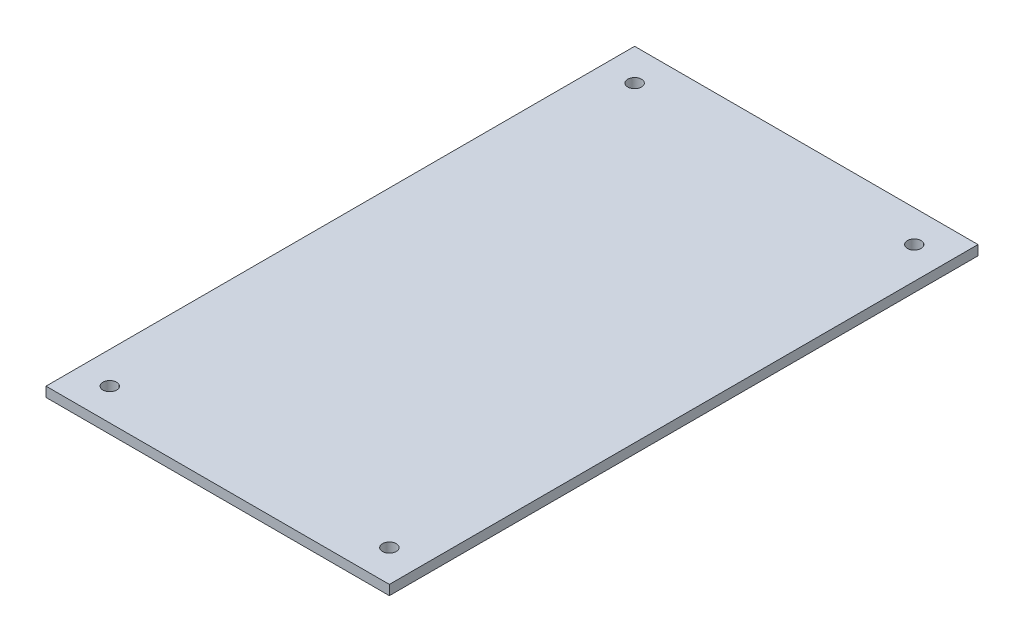
SolidWorks part; units mm, degrees
ref_plane "Спереди" through (0, 0, 0) normal (0, 0, 1) x (1, 0, 0)
ref_plane "Сверху" through (0, 0, 0) normal (0, 1, 0) x (1, 0, 0)
ref_plane "Справа" through (0, 0, 0) normal (1, 0, 0) x (0, 0, -1)
sketch "Эскиз1" plane through (0, 0, 0) normal (0, 1, 0) x (1, 0, 0)
  line L1 (32, -57) -> (-32, -57)
  line L2 (32, -57) -> (32, 57)
  line L3 (32, 57) -> (-32, 57)
  line L4 (-32, -57) -> (-32, 57)
  line L5 (32, -57) -> (-32, 57) construction
  line L6 (32, 57) -> (-32, -57) construction
  point P0 (0, 0)
  dimension "D1" = 64
  dimension "D2" = 114
extrude "Бобышка-Вытянуть1" add sketch "Эскиз1" along normal blind 2
sketch "Эскиз2" plane through (0, 2, 0) normal (0, 1, 0) x (1, 0, 0)
  line L1 (35, -60) -> (-35, -60)
  line L2 (35, -60) -> (35, 60)
  line L3 (35, 60) -> (-35, 60)
  line L4 (-35, -60) -> (-35, 60)
  line L5 (35, -60) -> (-35, 60) construction
  line L6 (35, 60) -> (-35, -60) construction
  point P0 (0, 0)
  dimension "D1" = 70
  dimension "D2" = 120
extrude "Бобышка-Вытянуть4" add sketch "Эскиз2" along normal blind 2
sketch "Эскиз4" plane through (0, 4, 0) normal (0, 1, 0) x (1, 0, 0)
  line L0 (-35, 60) -> (-35, -60) construction
  line L1 (35, 60) -> (-35, 60) construction
  line L2 (35, -60) -> (35, 60) construction
  line L3 (-35, -60) -> (35, -60) construction
  circle A0 centre (-28.5, 53.5) radius 1.4
  circle A1 centre (28.5, 53.5) radius 1.4
  circle A2 centre (-28.5, -53.5) radius 1.4
  circle A3 centre (28.5, -53.5) radius 1.4
  dimension "D1" = 6.5
  dimension "D3" = 2.8
  dimension "D6" = 2.8
  dimension "D9" = 2.8
  dimension "D12" = 2.8
  dimension "D2" = 6.5
  dimension "D4" = 6.5
  dimension "D5" = 6.5
  dimension "D7" = 6.5
  dimension "D8" = 6.5
  dimension "D10" = 6.5
  dimension "D11" = 6.5
extrude "Вырез-Вытянуть1" cut sketch "Эскиз4" against normal through all
